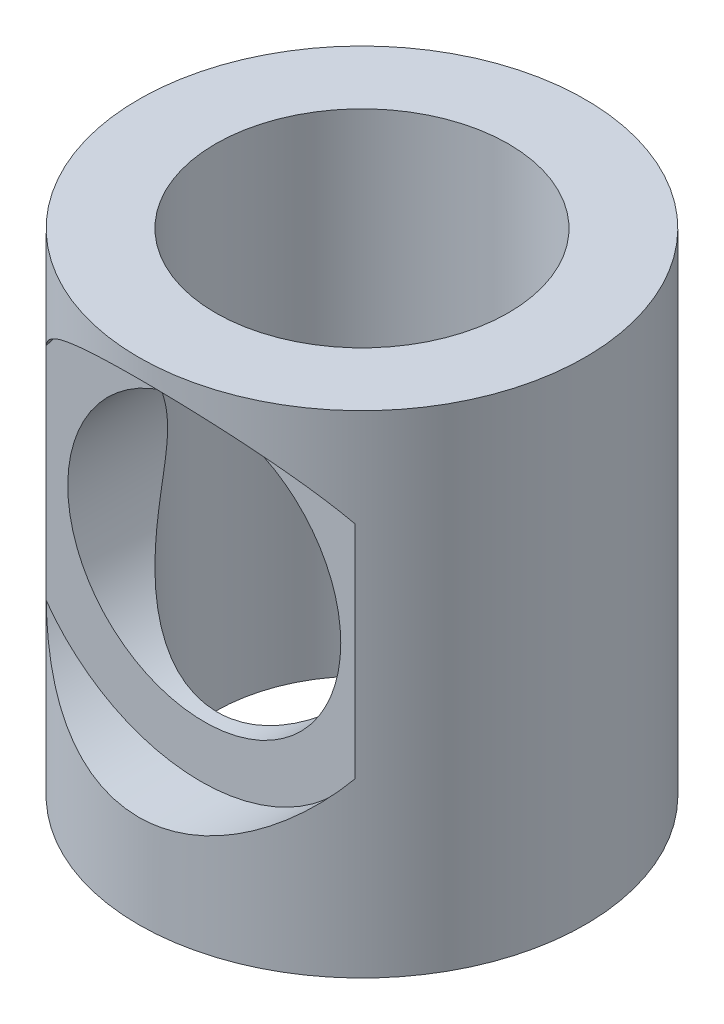
SolidWorks part; units mm, degrees
material "OMD-98"
ref_plane "Front Plane" through (0, 0, 0) normal (0, 0, 1) x (1, 0, 0)
ref_plane "Top Plane" through (0, 0, 0) normal (0, 1, 0) x (1, 0, 0)
ref_plane "Right Plane" through (0, 0, 0) normal (1, 0, 0) x (0, 0, -1)
sketch "Sketch1" plane through (0, 0, 0) normal (0, 1, 0) x (1, 0, 0)
  circle A0 centre (0, 0) radius 9
  circle A1 centre (0, 0) radius 5.9
  dimension "D1" = 18
  dimension "D2" = 11.8
extrude "Boss-Extrude1" add sketch "Sketch1" against normal blind 19.8
sketch "Sketch3" plane through (0, 0, 0) normal (0, 0, 1) x (1, 0, 0)
  line L1 (5.9, 0) -> (-5.9, 0) construction
  circle A0 centre (0, -8.4) radius 7.65
  dimension "D1" = 15.3
  dimension "D2" = 8.4
extrude "Cut-Extrude5" cut sketch "Sketch3" along normal through all from offset 6.5
sketch "Sketch6" plane through (0, 0, 6.5) normal (0, 0, 1) x (1, 0, 0)
  line L0 (-6.2249, -19.8) -> (6.2249, -19.8) construction
  line L1 (6.2249, 0) -> (6.2249, -19.8) construction
  circle A0 centre (0.1455, -8.4) radius 5.5
  dimension "D1" = 11
  dimension "D2" = 11.4
  dimension "D3" = 6.0795
extrude "Cut-Extrude6" cut sketch "Sketch6" against normal blind 7 and the other way through all
